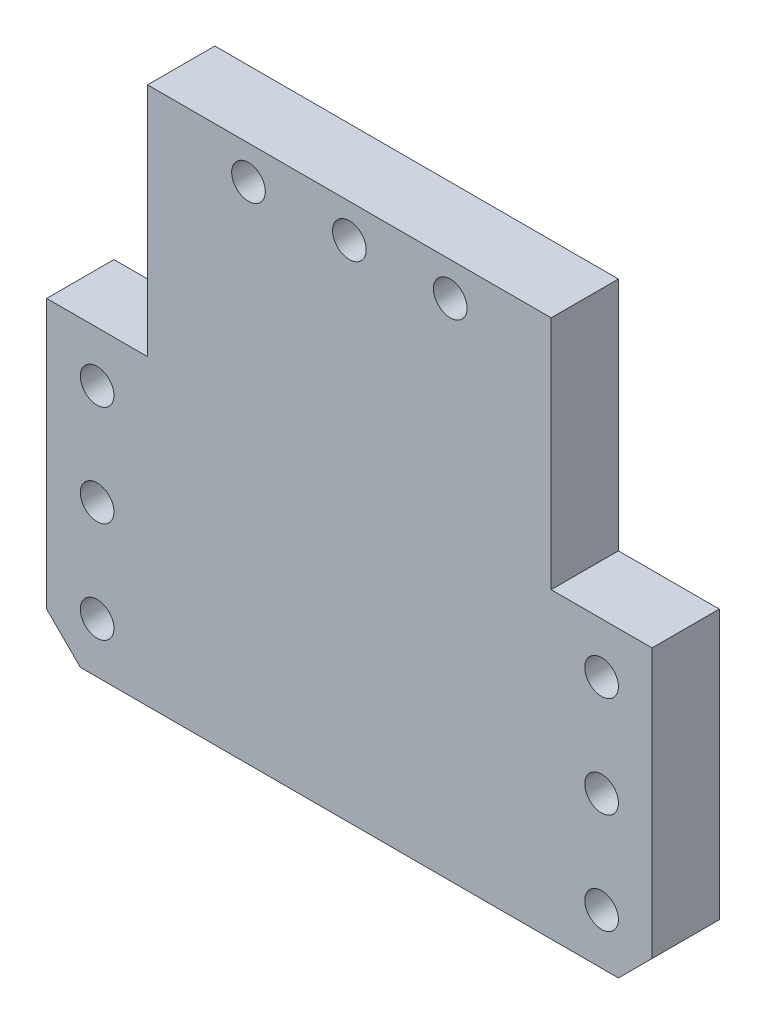
SolidWorks part; units mm, degrees
ref_plane "Plan de face" through (0, 0, 0) normal (0, 0, 1) x (1, 0, 0)
ref_plane "Plan de dessus" through (0, 0, 0) normal (0, 1, 0) x (1, 0, 0)
ref_plane "Plan de droite" through (0, 0, 0) normal (1, 0, 0) x (0, 0, -1)
sketch "Esquisse1" plane through (0, 0, 0) normal (0, 0, 1) x (1, 0, 0)
  line L1 (0, 0) -> (60, 0)
  line L2 (0, 0) -> (0, 80)
  line L3 (0, 80) -> (60, 80)
  line L4 (60, 0) -> (60, 80)
  dimension "D1" = 60
  dimension "D2" = 80
extrude "Boss.-Extru.1" add sketch "Esquisse1" along normal blind 10
sketch "Esquisse3" plane through (0, 0, 10) normal (0, 0, 1) x (1, 0, 0)
  line L0 (30, 0) -> (30, 80) construction
  line L1 (0, 0) -> (-15, 0)
  line L2 (0, 0) -> (0, 45)
  line L3 (0, 45) -> (-15, 45)
  line L4 (-15, 0) -> (-15, 45)
  line L5 (0, 0) -> (60, 0) construction
  line L6 (60, 80) -> (0, 80) construction
  line L7 (75, 0) -> (75, 45)
  line L8 (60, 45) -> (75, 45)
  line L9 (60, 0) -> (60, 45)
  line L10 (60, 0) -> (75, 0)
  dimension "D1" = 45
  dimension "D2" = 15
extrude "Boss.-Extru.2" add sketch "Esquisse3" against normal up to vertex (10 mm away) up to point (60, 80, 0)
sketch "Esquisse2" plane through (0, 0, 10) normal (0, 0, 1) x (1, 0, 0)
  line L0 (0, 75) -> (60, 75) construction
  line L1 (0, 80) -> (0, 45) construction
  line L2 (60, 45) -> (60, 80) construction
  line L3 (30, 75) -> (30, 80) construction
  line L4 (60, 80) -> (0, 80) construction
  line L5 (-7.5, 45) -> (-7.5, 0) construction
  line L6 (0, 45) -> (-15, 45) construction
  line L7 (-15, 0) -> (75, 0) construction
  line L8 (-7.5, 22.5) -> (-15, 22.5) construction
  line L9 (-15, 45) -> (-15, 0) construction
  circle A0 centre (45, 75) radius 2.5
  circle A1 centre (30, 75) radius 2.5
  circle A2 centre (15, 75) radius 2.5
  circle A3 centre (-7.5, 22.5) radius 2.5
  circle A4 centre (-7.5, 37.5) radius 2.5
  circle A5 centre (-7.5, 7.5) radius 2.5
  circle A6 centre (67.5, 7.5) radius 2.5
  circle A7 centre (67.5, 37.5) radius 2.5
  circle A8 centre (67.5, 22.5) radius 2.5
  dimension "D1" = 5
  dimension "D2" = 15
  dimension "D3" = 5
  dimension "D4" = 15
extrude "Enlèv. mat.-Extru.1" cut sketch "Esquisse2" against normal up to vertex (10 mm away)
chamfer "Chanfrein1" distance 5 angle 45 2 edges at (75, 0, 5) (-15, 0, 5)
